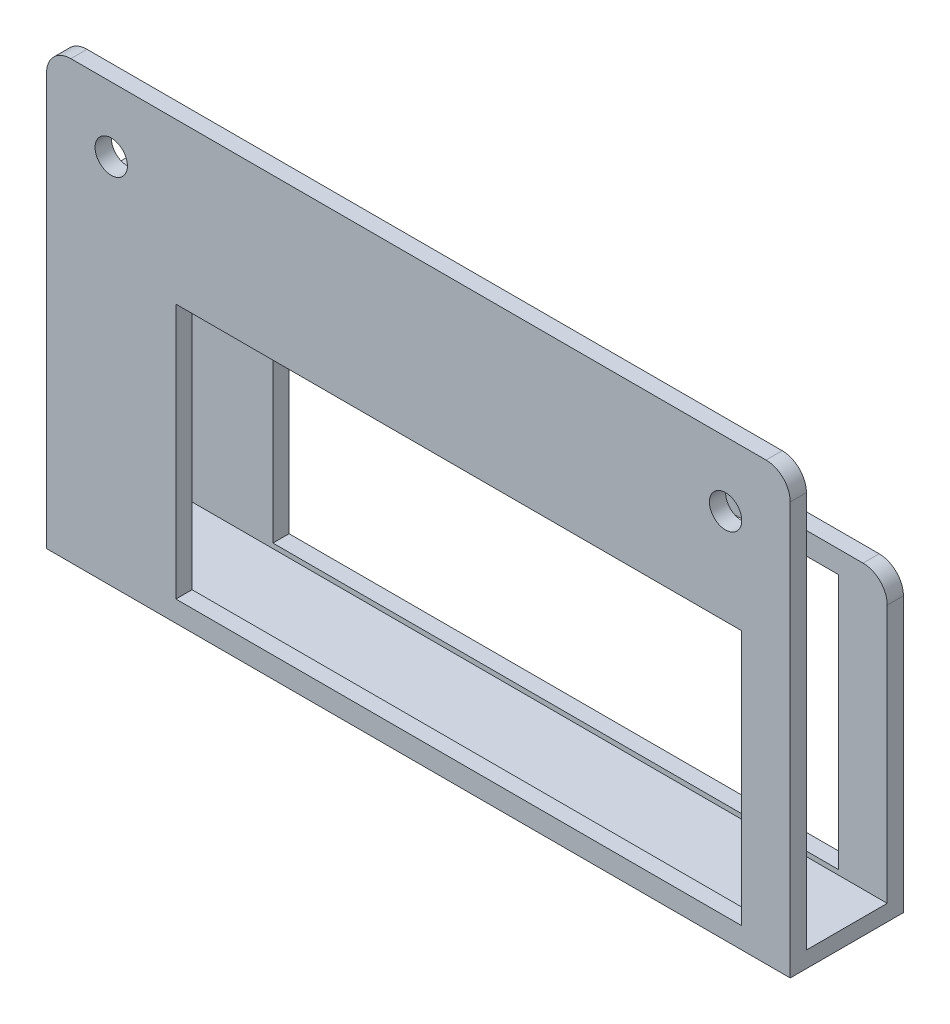
SolidWorks part; units mm, degrees
ref_plane "Alzado" through (0, 0, 0) normal (0, 0, 1) x (1, 0, 0)
ref_plane "Planta" through (0, 0, 0) normal (0, 1, 0) x (1, 0, 0)
ref_plane "Vista lateral" through (0, 0, 0) normal (1, 0, 0) x (0, 0, -1)
sketch "Croquis1" plane through (0, 0, 0) normal (0, 0, 1) x (1, 0, 0)
  line L1 (-92, 54) -> (0, 54)
  line L2 (-92, 54) -> (-92, 0)
  line L3 (-92, 0) -> (0, 0)
  line L4 (0, 54) -> (0, 0)
  line L5 (-92, 54) -> (0, 0) construction
  line L6 (-92, 0) -> (0, 54) construction
  line L7 (-76, 34.2) -> (-6, 34.2)
  line L8 (-76, 34.2) -> (-76, 2.6)
  line L9 (-76, 2.6) -> (-6, 2.6)
  line L10 (-6, 34.2) -> (-6, 2.6)
  line L11 (-76, 34.2) -> (-6, 2.6) construction
  line L12 (-76, 2.6) -> (-6, 34.2) construction
  circle A0 centre (-84, 46) radius 2
  circle A1 centre (-8, 46) radius 2
  point P0 (-46, 27)
  point P6 (-41, 18.4)
  dimension "D7" = 4
  dimension "D8" = 4
  dimension "D9" = 8
  dimension "D1" = 2.6
  dimension "D2" = 34.2
  dimension "D3" = 54
  dimension "D4" = 92
  dimension "D5" = 6
  dimension "D6" = 70
  dimension "D10" = 8
  dimension "D11" = 8
  dimension "D12" = 8
extrude "Saliente-Extruir1" add sketch "Croquis1" along normal blind 14
sketch "Croquis2" plane through (0, 0, 0) normal (1, 0, 0) x (0, 0, -1)
  line L0 (-2, 36.9531) -> (-2, 2)
  line L1 (-14, 54) -> (0, 54) construction
  line L2 (-2, 2) -> (-12, 2)
  line L3 (-12, 2) -> (-12, 36.9531)
  line L5 (-14, 0) -> (-14, 54) construction
  line L7 (-12, 54) -> (-2, 54)
  line L8 (0, 0) -> (0, 54) construction
  line L9 (-14, 0) -> (0, 0) construction
  line L10 (-12, 36.9531) -> (-12, 54)
  line L11 (-2, 36.9531) -> (0, 36.9531)
  line L12 (0, 36.9531) -> (0, 54)
  line L13 (-2, 54) -> (0, 54)
  dimension "D1" = 2
  dimension "D2" = 2
  dimension "D3" = 2
extrude "Cortar-Extruir1" cut sketch "Croquis2" against normal blind 90
sketch "Croquis3" plane through (0, 0, 0) normal (0, 0, -1) x (-1, 0, 0)
  line L1 (90, 36.9531) -> (92, 36.9531)
  line L2 (90, 36.9531) -> (90, 54)
  line L3 (90, 54) -> (92, 54)
  line L4 (92, 36.9531) -> (92, 54)
extrude "Cortar-Extruir2" cut sketch "Croquis3" against normal up to surface (12 mm away) up to face at (-41, 18.4, 12)
sketch "Croquis4" plane through (-92, 0, 0) normal (-1, 0, 0) x (0, 0, 1)
  line L0 (14, 54) -> (14, 0) construction
  line L1 (3, 2.3409) -> (11, 2.3409)
  line L2 (3, 2.3409) -> (3, 15.3409)
  line L3 (3, 15.3409) -> (11, 15.3409)
  line L4 (11, 2.3409) -> (11, 15.3409)
  line L5 (0, 36.9531) -> (0, 0) construction
  dimension "D1" = 13
  dimension "D2" = 3
  dimension "D3" = 3
extrude "Cortar-Extruir3" cut sketch "Croquis4" against normal up to surface (2 mm away) up to face at (-90, 19.4765, 7)
fillet "Redondeo1" radius 3 1 edges at (-92, 54, 13)
fillet "Redondeo2" radius 3 1 edges at (0, 54, 13)
fillet "Redondeo3" radius 3 1 edges at (0, 36.9531, 1)
